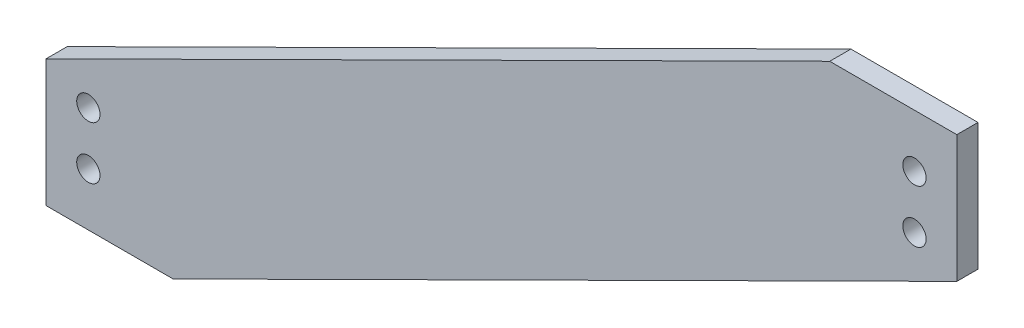
SolidWorks part; units mm, degrees
ref_plane "Front" through (0, 0, 0) normal (0, 0, 1) x (1, 0, 0)
ref_plane "Top" through (0, 0, 0) normal (0, 1, 0) x (1, 0, 0)
ref_plane "Right" through (0, 0, 0) normal (1, 0, 0) x (0, 0, -1)
sketch "Sketch1" plane through (0, 0, 0) normal (0, 0, 1) x (1, 0, 0)
  line L0 (0, 0) -> (20, 0)
  line L1 (20, 0) -> (215, 122)
  line L2 (215, 122) -> (195, 122)
  line L3 (195, 122) -> (0, 0)
  dimension "D1" = 20
  dimension "D2" = 122
  dimension "D3" = 215
extrude "Boss-Extrude1" add sketch "Sketch1" along normal blind 5
sketch "Sketch2" plane through (0, 0, 5) normal (0, 0, 1) x (1, 0, 0)
  line L0 (0, 0) -> (0, 30)
  line L1 (0, 30) -> (185, 122)
  line L2 (0, 0) -> (30, 0)
  line L3 (195, 122) -> (185, 122)
  line L4 (215, 122) -> (215, 92)
  line L5 (215, 92) -> (30, 0)
  line L8 (195, 122) -> (215, 122)
  dimension "D1" = 30
  dimension "D2" = 30
  dimension "D3" = 30
extrude "Boss-Extrude2" add sketch "Sketch2" against normal up to surface (5 mm away) up to face at (107.5, 61, 0)
hole_wizard "M5 Clearance Hole1" positions "Sketch3" profile "Sketch4" hole size "M5" standard "ISO" end condition through all
sketch "Sketch3" plane through (0, 0, 5) normal (0, 0, 1) x (1, 0, 0)
  line L0 (0, 30) -> (0, 0) construction
  line L1 (0, 0) -> (30, 0) construction
  line L2 (215, 122) -> (185, 122) construction
  line L3 (215, 92) -> (215, 122) construction
  line L4 (10, 25) -> (10, 0) construction
  line L6 (205, 97) -> (205, 122) construction
  point P0 (205, 97)
  point P2 (10, 25)
  point P20 (10, 12.5)
  point P22 (205, 109.5)
  dimension "D1" = 10
  dimension "D2" = 25
  dimension "D3" = 25
  dimension "D4" = 10
sketch "Sketch4" plane through (205, 97, 5) normal (1, 0, 0) x (0, -1, 0)
  line L0 (0, 0) -> (0, 5)
  line L1 (0, 5) -> (2.75, 5)
  line L2 (2.75, 5) -> (2.75, 0)
  line L5 (2.75, 0) -> (0, 0)
  line L11 (0, -6.35) -> (0, 107.95) construction
  dimension "Thru Hole Dia." = 5.5
  dimension "Thru Hole Depth" = 5
